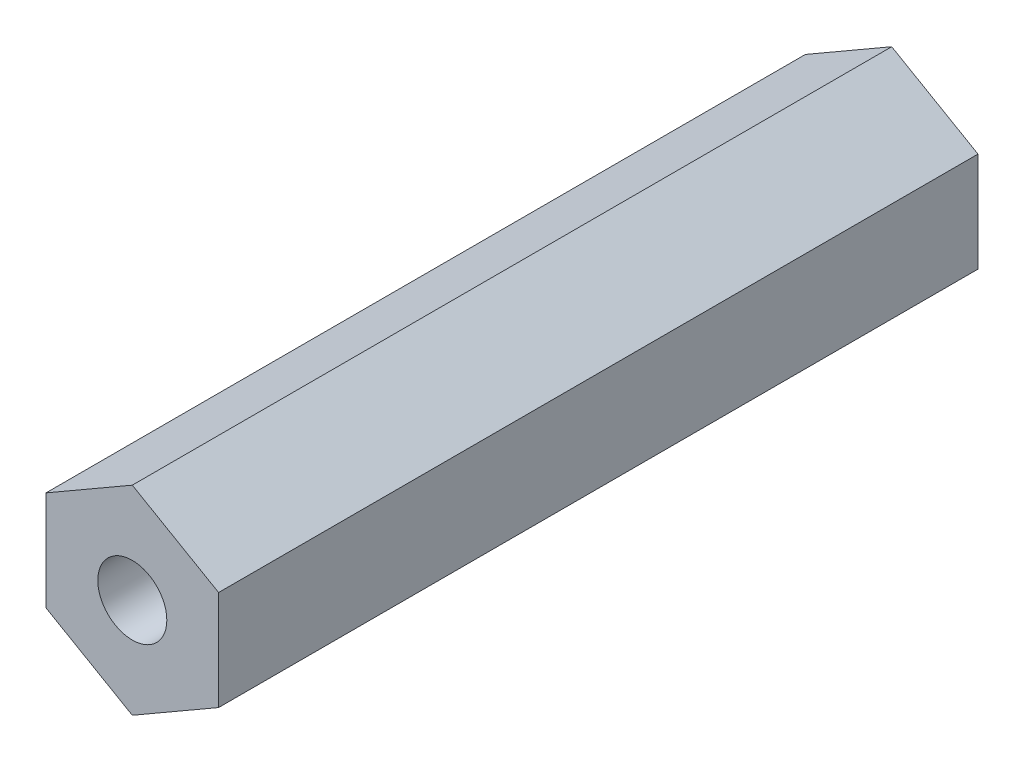
SolidWorks part; units mm, degrees
ref_plane "Front Plane" through (0, 0, 0) normal (0, 0, 1) x (1, 0, 0)
ref_plane "Top Plane" through (0, 0, 0) normal (0, 1, 0) x (1, 0, 0)
ref_plane "Right Plane" through (0, 0, 0) normal (1, 0, 0) x (0, 0, -1)
sketch "Sketch1" plane through (0, 0, 0) normal (0, 0, 1) x (1, 0, 0)
  line L1 (0, 2.8868) -> (-2.5, 1.4434)
  line L2 (-2.5, 1.4434) -> (-2.5, -1.4434)
  line L3 (-2.5, -1.4434) -> (0, -2.8868)
  line L4 (0, -2.8868) -> (2.5, -1.4434)
  line L5 (2.5, -1.4434) -> (2.5, 1.4434)
  line L6 (2.5, 1.4434) -> (0, 2.8868)
  circle A0 centre (0, 0) radius 2.5 construction
  circle A1 centre (0, 0) radius 1
  dimension "D1" = 5
  dimension "D2" = 2
extrude "Boss-Extrude1" add sketch "Sketch1" along normal blind 22
